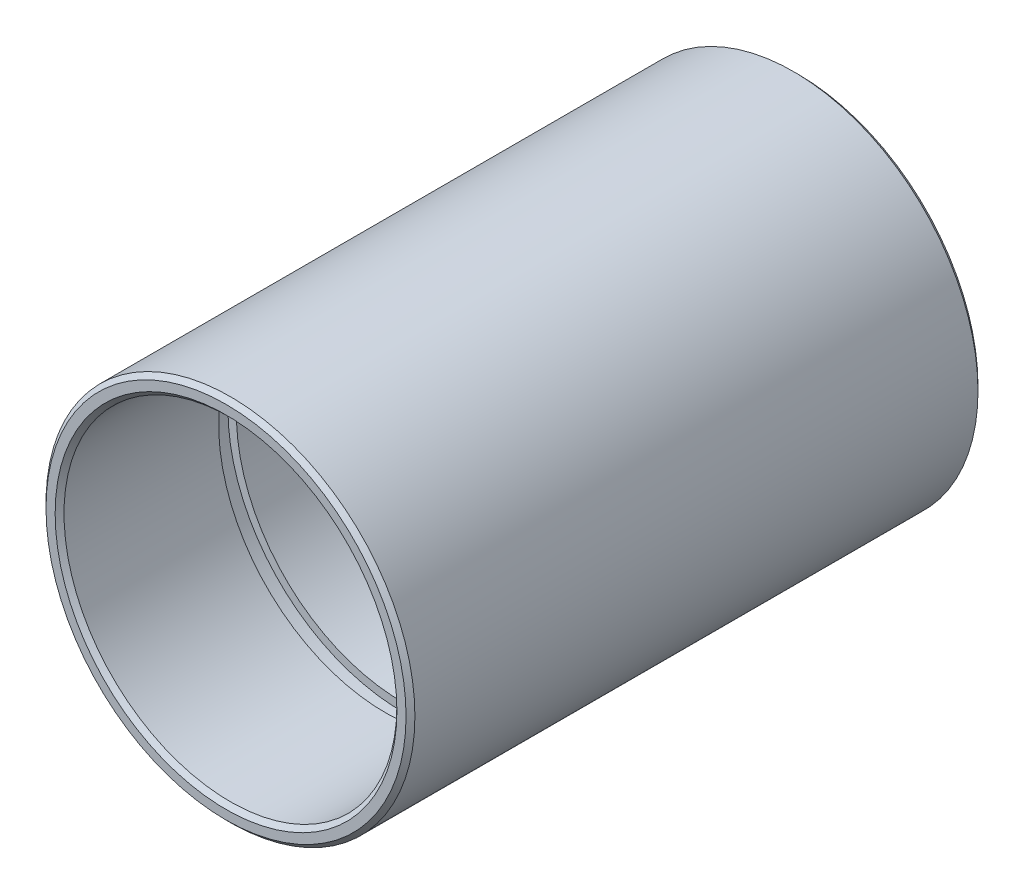
SolidWorks part; units mm, degrees
ref_plane "Front" through (0, 0, 0) normal (0, 0, 1) x (1, 0, 0)
ref_plane "Top" through (0, 0, 0) normal (0, 1, 0) x (1, 0, 0)
ref_plane "Right" through (0, 0, 0) normal (1, 0, 0) x (0, 0, -1)
sketch "Sketch1" plane through (0, 0, 0) normal (0, 0, 1) x (1, 0, 0)
  circle A0 centre (0, 0) radius 14.3256
  circle A1 centre (0, 0) radius 15.875
  dimension "D1" = 28.6512
  dimension "D2" = 31.75
extrude "Base-Extrude" add sketch "Sketch1" along normal blind 49.2252
chamfer "Chamfer1" distance 0.381 angle 45 4 edges at (15.875, 0, 0) (15.875, 0, 49.2252) (14.3256, 0, 0) (14.3256, 0, 49.2252)
ref_plane "Plane4" through (0, 0, 15.2146) normal (0, 0, 1) x (1, 0, 0)
sketch "Sketch2" plane through (0, 0, 15.2146) normal (0, 0, 1) x (1, 0, 0)
  circle A0 centre (0, 0) radius 15.0495
  dimension "D1" = 30.099
extrude "Cut-Extrude1" cut sketch "Sketch2" against normal blind 1.524
ref_plane "Plane5" through (0, 0, 34.0106) normal (0, 0, 1) x (1, 0, 0)
sketch "Sketch3" plane through (0, 0, 34.0106) normal (0, 0, 1) x (1, 0, 0)
  circle A0 centre (0, 0) radius 15.0495
  dimension "D1" = 30.099
extrude "Cut-Extrude2" cut sketch "Sketch3" along normal blind 1.524
